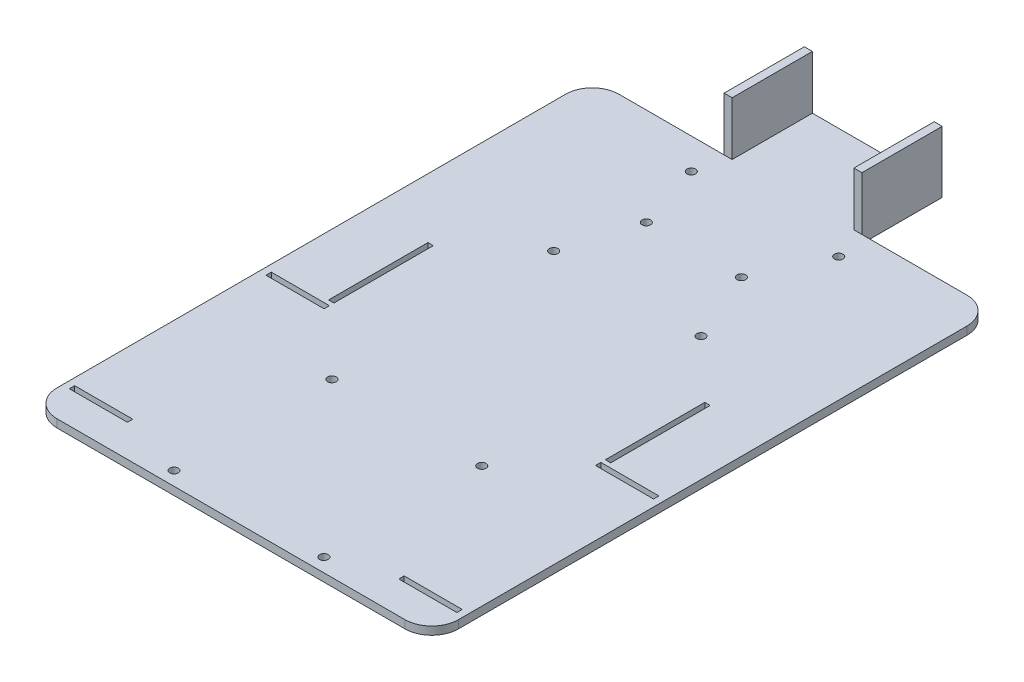
SolidWorks part; units mm, degrees
ref_plane "Front Plane" through (0, 0, 0) normal (0, 0, 1) x (1, 0, 0)
ref_plane "Top Plane" through (0, 0, 0) normal (0, 1, 0) x (1, 0, 0)
ref_plane "Right Plane" through (0, 0, 0) normal (1, 0, 0) x (0, 0, -1)
sketch "Sketch1" plane through (0, 0, 0) normal (0, 1, 0) x (1, 0, 0)
  line L0 (0, -1105) -> (0, 0) construction
  line L1 (-75, 105) -> (-25.75, 105)
  line L2 (-75, 105) -> (-75, -105)
  line L3 (-75, -105) -> (75, -105)
  line L4 (75, 105) -> (75, -105)
  line L5 (-75, 105) -> (75, -105) construction
  line L6 (-75, -105) -> (75, 105) construction
  line L7 (25.75, 105) -> (75, 105)
  line L9 (-25.75, 105) -> (-25.75, 135)
  line L10 (-25.75, 135) -> (25.75, 135)
  line L11 (25.75, 105) -> (25.75, 135)
  line L14 (0, 135) -> (0, 1140.484) construction
  point P0 (0, 0)
  point P12 (0, 120)
  dimension "D1" = 210
  dimension "D2" = 150
  dimension "D3" = 30
  dimension "D4" = 51.5
extrude "Boss-Extrude1" add sketch "Sketch1" along normal blind 3
sketch "Sketch2" plane through (0, 3, 0) normal (0, 1, 0) x (1, 0, 0)
  line L0 (0, 0) -> (0, -24.7531) construction
  line L1 (0, -19.5235) -> (6.8494, -19.5235) construction
  line L2 (72.4126, -17.5235) -> (50.7125, -17.5235)
  line L3 (-72.4126, -19.5235) -> (-50.7125, -19.5235)
  line L4 (-72.4126, -19.5235) -> (-72.4126, -17.5235)
  line L5 (-72.4126, -17.5235) -> (-50.7125, -17.5235)
  line L6 (-50.7125, -19.5235) -> (-50.7125, -17.5235)
  line L7 (50.7125, -19.5235) -> (50.7125, -17.5235)
  line L8 (72.4126, -19.5235) -> (50.7125, -19.5235)
  line L9 (72.4126, -19.5235) -> (72.4126, -17.5235)
  line L10 (-0.7291, 2.7433) -> (67.8805, 2.7433) construction
  line L11 (52.7125, 21.3067) -> (50.7125, 21.3067)
  line L12 (-52.7125, -15.8202) -> (-50.7125, -15.8202)
  line L13 (-52.7125, -15.8202) -> (-52.7125, 21.3067)
  line L14 (-52.7125, 21.3067) -> (-50.7125, 21.3067)
  line L15 (-50.7125, -15.8202) -> (-50.7125, 21.3067)
  line L16 (-52.7125, -15.8202) -> (-50.7125, 21.3067) construction
  line L17 (-52.7125, 21.3067) -> (-50.7125, -15.8202) construction
  line L18 (50.7125, -15.8202) -> (50.7125, 21.3067)
  line L19 (52.7125, -15.8202) -> (50.7125, -15.8202)
  line L20 (52.7125, -15.8202) -> (52.7125, 21.3067)
  line L21 (52.7125, 21.3067) -> (50.7125, -15.8202) construction
  line L22 (52.7125, -15.8202) -> (50.7125, 21.3067) construction
  line L23 (0, -90.9939) -> (-70.1825, -90.9939) construction
  line L24 (50.7125, -90.9939) -> (50.7125, -92.9939)
  line L25 (-72.4126, -90.9939) -> (-50.7125, -90.9939)
  line L26 (-72.4126, -90.9939) -> (-72.4126, -92.9939)
  line L27 (-72.4126, -92.9939) -> (-50.7125, -92.9939)
  line L28 (-50.7125, -90.9939) -> (-50.7125, -92.9939)
  line L29 (72.4126, -90.9939) -> (72.4126, -92.9939)
  line L30 (72.4126, -92.9939) -> (50.7125, -92.9939)
  line L31 (72.4126, -90.9939) -> (50.7125, -90.9939)
  circle A0 centre (-26.5003, 93.5057) radius 1.6
  circle A1 centre (28.5697, 93.5057) radius 1.6
  circle A2 centre (28.5697, 42.0657) radius 1.6
  circle A3 centre (-26.5003, 42.0657) radius 1.6
  circle A4 centre (-26.3983, -40.8915) radius 1.6
  circle A5 centre (29.6017, -40.8915) radius 1.6
  circle A6 centre (-26.3983, -99.8915) radius 1.6
  circle A8 centre (29.6017, -99.8915) radius 1.6
  point P39 (-51.7125, 2.7433)
  point P50 (51.7125, 2.7433)
  dimension "D1" = 2
  dimension "D2" = 2
  dimension "D3" = 2
extrude "Cut-Extrude1" cut sketch "Sketch2" against normal through all
sketch "Sketch3" plane through (0, 3, 0) normal (0, 1, 0) x (1, 0, 0)
  line L0 (25.75, 135) -> (-25.75, 135) construction
  line L1 (-25.75, 105) -> (-22.75, 105)
  line L2 (-25.75, 105) -> (-25.75, 135)
  line L3 (-25.75, 135) -> (-22.75, 135)
  line L4 (-22.75, 105) -> (-22.75, 135)
  line L5 (-25.75, 105) -> (-22.75, 135) construction
  line L6 (-25.75, 135) -> (-22.75, 105) construction
  line L8 (25.75, 105) -> (22.75, 105)
  line L9 (25.75, 105) -> (25.75, 135)
  line L10 (25.75, 135) -> (22.75, 135)
  line L11 (22.75, 105) -> (22.75, 135)
  line L12 (25.75, 105) -> (22.75, 135) construction
  line L13 (25.75, 135) -> (22.75, 105) construction
  point P4 (-24.25, 120)
  point P12 (24.25, 120)
  dimension "D1" = 3
  dimension "D2" = 3
extrude "Boss-Extrude2" add sketch "Sketch3" along normal blind 20
sketch "Sketch4" plane through (0, 0, 0) normal (0, -1, 0) x (1, 0, 0)
  line L0 (-0.7027, -1.093) -> (-0.7027, 86.3029) construction
  line L2 (-25.7027, -53.6321) -> (24.2973, -53.6321)
  line L3 (-25.7027, -53.6321) -> (-25.7027, -83.6321)
  line L4 (-25.7027, -83.6321) -> (24.2973, -83.6321)
  line L5 (24.2973, -53.6321) -> (24.2973, -83.6321)
  line L6 (-25.7027, -53.6321) -> (24.2973, -83.6321) construction
  line L7 (-25.7027, -83.6321) -> (24.2973, -53.6321) construction
  point P1 (-0.7027, -68.6321)
  dimension "D1" = 30
  dimension "D2" = 50
fillet "Fillet2" radius 10 4 edges at (-75, 1.5, 105) (75, 1.5, 105) (75, 1.5, -105) (-75, 1.5, -105)
sketch "Sketch5" plane through (0, 0, 0) normal (0, -1, 0) x (1, 0, 0)
  line L0 (1.2532, -68.6321) -> (43.1827, -68.6321) construction
  line L7 (24.2973, -53.6321) -> (24.2973, -83.6321) construction
  circle A0 centre (-18.4527, -68.6321) radius 1.6
  circle A1 centre (17.0473, -68.6321) radius 1.6
  dimension "D1" = 3.2
  dimension "D2" = 3.2
  dimension "D3" = 35.5
  dimension "D4" = 7.25
extrude "Cut-Extrude2" cut sketch "Sketch5" against normal through all both and the other way through all
